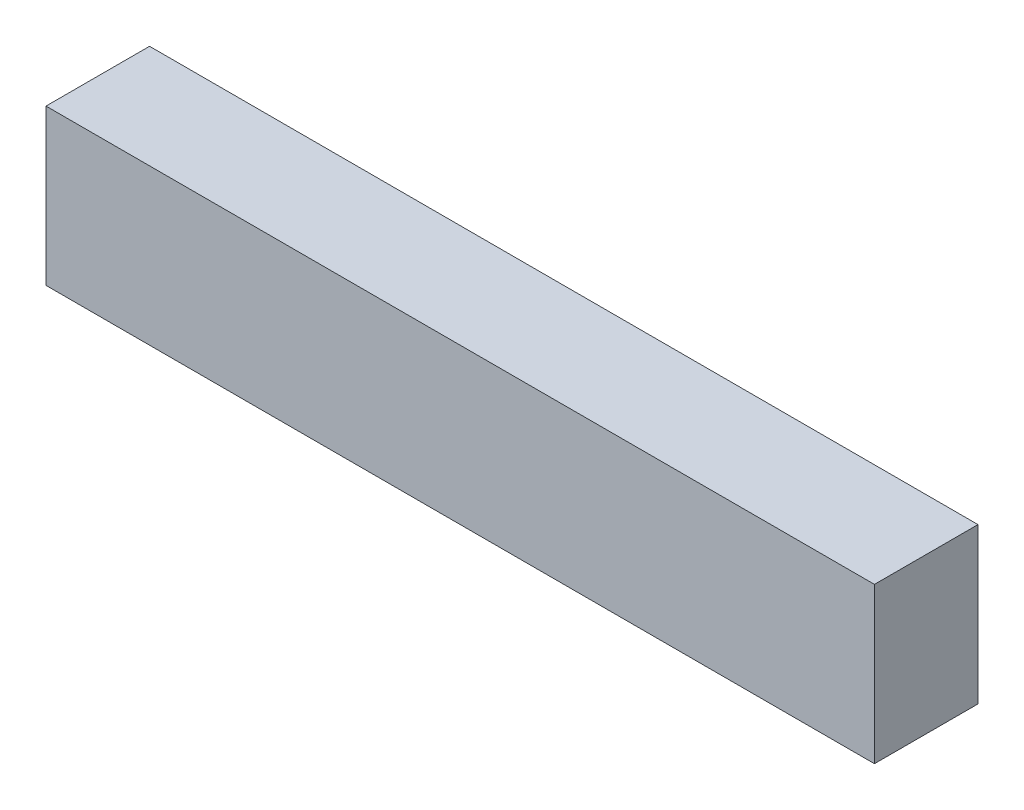
SolidWorks part; units mm, degrees
ref_plane "前视基准面" through (0, 0, 0) normal (0, 0, 1) x (1, 0, 0)
ref_plane "上视基准面" through (0, 0, 0) normal (0, 1, 0) x (1, 0, 0)
ref_plane "右视基准面" through (0, 0, 0) normal (1, 0, 0) x (0, 0, -1)
other "Configuration Table"
sketch "草图1" plane through (0, 0, 0) normal (0, 0, 1) x (1, 0, 0)
  line L1 (-4, 0.75) -> (4, 0.75)
  line L2 (-4, 0.75) -> (-4, -0.75)
  line L3 (-4, -0.75) -> (4, -0.75)
  line L4 (4, 0.75) -> (4, -0.75)
  line L5 (-4, 0.75) -> (4, -0.75) construction
  line L6 (-4, -0.75) -> (4, 0.75) construction
  point P0 (0, 0)
  dimension "D1" = 1.5
  dimension "D2" = 8
extrude "凸台-拉伸1" add sketch "草图1" along normal blind 1
